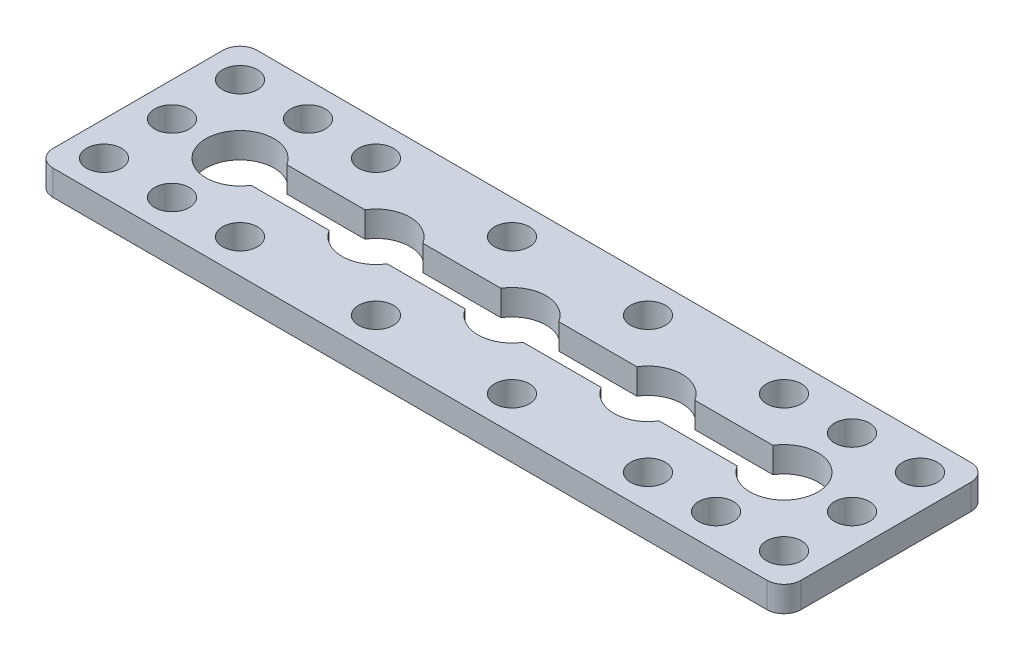
SolidWorks part; units mm, degrees
ref_plane "前视" through (0, 0, 0) normal (0, 0, 1) x (1, 0, 0)
ref_plane "上视" through (0, 0, 0) normal (0, 1, 0) x (1, 0, 0)
ref_plane "右视" through (0, 0, 0) normal (1, 0, 0) x (0, 0, -1)
sketch "草图1" plane through (0, 0, 0) normal (1, 0, 0) x (0, 0, -1)
  line L1 (-12, 1.5) -> (12, 1.5)
  line L2 (-12, 1.5) -> (-12, -1.5)
  line L3 (-12, -1.5) -> (12, -1.5)
  line L4 (12, 1.5) -> (12, -1.5)
  line L5 (-12, 1.5) -> (12, -1.5) construction
  line L6 (-12, -1.5) -> (12, 1.5) construction
  point P0 (0, 0)
  dimension "D1" = 24
  dimension "D2" = 3
extrude "凸台-拉伸1" add sketch "草图1" along normal blind 88
fillet "圆角1" radius 2 4 edges at (0, 0, -12) (88, 0, -12) (0, 0, 12) (88, 0, 12)
sketch "草图3" plane through (0, 1.5, 0) normal (0, 1, 0) x (1, 0, 0)
  line L0 (0, 10) -> (0, -10) construction
  line L1 (86, 12) -> (2, 12) construction
  line L2 (86, -12) -> (2, -12) construction
  circle A0 centre (4, 8) radius 2.05
  circle A1 centre (4, -8) radius 2.05
  dimension "D1" = 4.1
  dimension "D3" = 4
  dimension "D4" = 4
  dimension "D2" = 4
extrude "切除-拉伸1" cut sketch "草图3" against normal through all
sketch "草图4" plane through (0, 1.5, 0) normal (0, 1, 0) x (1, 0, 0)
  line L0 (0, 10) -> (0, -10) construction
  circle A0 centre (12, 0) radius 4
  dimension "D1" = 8
  dimension "D2" = 12
extrude "切除-拉伸2" cut sketch "草图4" against normal through all
pattern_linear "阵列(线性)1" count 12 spacing 16 along (1, 0, 0) of "切除-拉伸1"
pattern_linear "阵列(线性)2" count 11 spacing 16 along (1, 0, 0) of "切除-拉伸2"
sketch "草图5" plane through (0, 1.5, 0) normal (0, 1, 0) x (1, 0, 0)
  line L0 (0, 10) -> (0, -10) construction
  line L1 (88, 10) -> (88, -10) construction
  circle A0 centre (4, 0) radius 2.05
  circle A1 centre (84, 0) radius 2.05
  dimension "D1" = 4.1
  dimension "D2" = 4
  dimension "D3" = 4
extrude "切除-拉伸3" cut sketch "草图5" against normal through all
ref_plane "基准面1" through (12, 0, 0) normal (-1, 0, 0) x (0, 0, 1)
sketch "草图6" plane through (12, 0, 0) normal (-1, 0, 0) x (0, 0, 1)
  line L0 (-10, 1.5) -> (10, 1.5) construction
  line L1 (-2.1, -1.5) -> (2.1, -1.5)
  line L2 (-2.1, -1.5) -> (-2.1, 1.5)
  line L3 (-2.1, 1.5) -> (2.1, 1.5)
  line L4 (2.1, -1.5) -> (2.1, 1.5)
  line L5 (-2.1, -1.5) -> (2.1, 1.5) construction
  line L6 (-2.1, 1.5) -> (2.1, -1.5) construction
  point P0 (0, 0)
  dimension "D1" = 4.2
extrude "切除-拉伸4" cut sketch "草图6" against normal blind 66
ref_plane "基准面3" through (0, -57.5, 0) normal (0, -1, 0) x (-1, 0, 0)
sketch "草图7" plane through (0, 1.5, 0) normal (0, 1, 0) x (1, 0, 0)
  line L0 (4, -8) -> (12, -8) construction
  line L1 (12, -8) -> (12, 8) construction
  circle A0 centre (12, 8) radius 2.05
  circle A1 centre (12, -8) radius 2.05
  circle A2 centre (20, 8) radius 2.05 construction
  circle A3 centre (20, -8) radius 2.05 construction
  circle A4 centre (4, 0) radius 2.05 construction
  dimension "D1" = 8
  dimension "D2" = 8
extrude "切除-拉伸5" cut sketch "草图7" against normal blind 10
ref_plane "基准面4" through (44, 0, 0) normal (-1, 0, 0) x (0, 0, 1)
mirror "镜向1" about plane through (44, 0, 0) normal (-1, 0, 0) of "切除-拉伸5"
